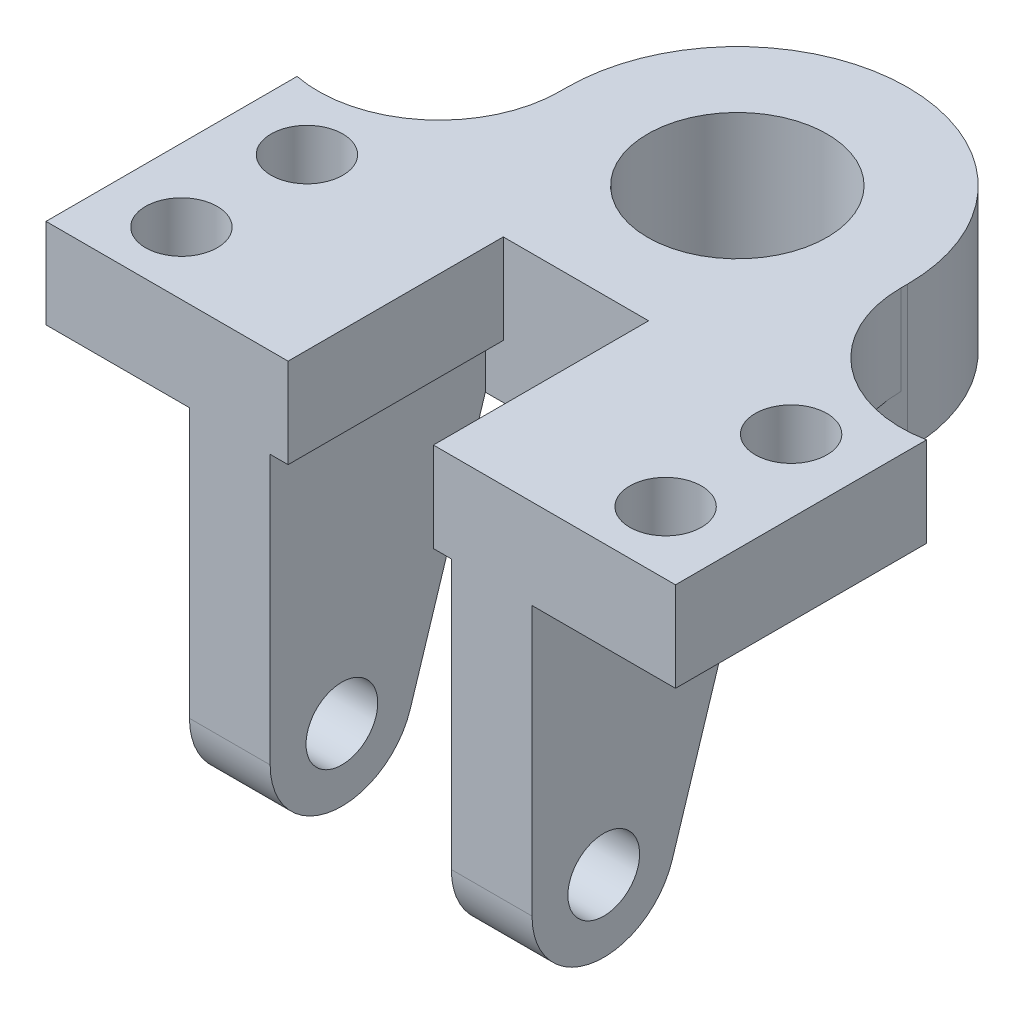
SolidWorks part; units mm, degrees
ref_plane "Front Plane" through (0, 0, 0) normal (0, 0, 1) x (1, 0, 0)
ref_plane "Top Plane" through (0, 0, 0) normal (0, 1, 0) x (1, 0, 0)
ref_plane "Right Plane" through (0, 0, 0) normal (1, 0, 0) x (0, 0, -1)
sketch "Sketch1" plane through (0, 0, 0) normal (0, 1, 0) x (1, 0, 0)
  line L0 (-38, -36) -> (38, -36)
  line L1 (38, 0) -> (38, -36)
  line L3 (-38, -36) -> (-38, 0)
  circle A11 centre (0, 0) radius 20
  arc A12 (38, 0) -> (-38, 0) centre (0, 0) ccw
  point P2 (0, 0)
  dimension "D1" = 38
  dimension "D2" = 40
  dimension "D3" = 36
extrude "Boss-Extrude1" add sketch "Sketch1" along normal blind 32
sketch "Sketch2" plane through (0, 32, 0) normal (0, 1, 0) x (1, 0, 0)
  line L0 (-16.2058, -84) -> (-38.2058, -84)
  line L1 (-38, -36) -> (38, -36) construction
  line L2 (-38.2058, -84) -> (-70.2058, -84)
  line L3 (-16.2058, -84) -> (-16.2058, -36)
  line L4 (-70.2058, -84) -> (-70.2058, -28)
  line L5 (-38, 0) -> (-38, -36) construction
  line L6 (-38, -36) -> (38, -36) construction
  line L7 (-38, -1.5187) -> (-38, -36)
  line L8 (-38, -36) -> (-16.2058, -36)
  circle A0 centre (-54, -42) radius 8
  circle A1 centre (-54, -70) radius 8
  arc A2 (-70.2058, -28) -> (-38, -1.5187) centre (-64.9901, -1.5187) ccw
  point P15 (0, 0)
  point P16 (0, 0)
  point P20 (0, 0)
  point P22 (0, 0)
  point P23 (0, 0)
  point P24 (0, 0)
  point P25 (0, 0)
  dimension "D1" = 56
  dimension "D2" = 28
  dimension "D3" = 32
  dimension "D4" = 14
  dimension "D5" = 48
extrude "Boss-Extrude3" add sketch "Sketch2" against normal blind 20
mirror "Mirror1" about plane through (0, 0, 0) normal (1, 0, 0) of "Boss-Extrude3"
sketch "Sketch11" plane through (16.2058, 0, 0) normal (-1, 0, 0) x (0, 0, 1)
  line L0 (28, 12) -> (84, 12) construction
  line L1 (36, 12) -> (84, 12)
  line L2 (84, 12) -> (84, -48)
  line L3 (52.7479, -52.8347) -> (36, 0)
  line L4 (36, 12) -> (36, 0) construction
  line L5 (36, 12) -> (36, 0)
  line L6 (28, 32) -> (84, 32) construction
  arc A0 (84, -48) -> (52.7479, -52.8347) centre (68, -48) cw
  circle A1 centre (68, -48) radius 8
  dimension "D1" = 80
  dimension "D2" = 16
  dimension "D3" = 16
extrude "Boss-Extrude4" add sketch "Sketch11" against normal blind 18 from offset 4 offset against normal yes
mirror "Mirror2" about plane through (0, 0, 0) normal (1, 0, 0) of "Boss-Extrude4"
